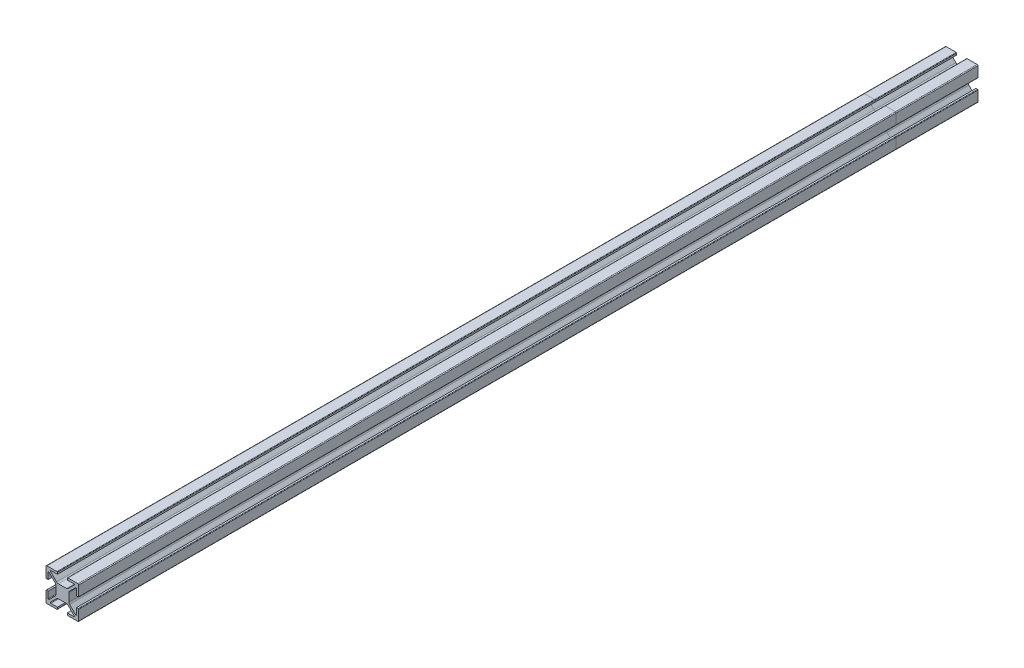
SolidWorks part; units mm, degrees
material "6063-T5"
material "6063-T5"
ref_plane "Front" through (0, 0, 0) normal (0, 0, 1) x (1, 0, 0)
ref_plane "Top" through (0, 0, 0) normal (0, 1, 0) x (1, 0, 0)
ref_plane "Right" through (0, 0, 0) normal (1, 0, 0) x (0, 0, -1)
sketch "Esboço1" plane through (0, 0, 0) normal (1, 0, 0) x (0, 0, -1)
  line L0 (0, 0) -> (-50, 0)
  dimension "D1" = 50
other "Quadrado PF20-21 - PERFIL 2020 T-SLOT 6MM(1)"
ref_plane "Plano1" through (0, 0, 0) normal (0, 0, 1) x (0, -1, 0)
sketch "Esboço11" plane through (0, 0, 0) normal (0, 0, 1) x (0, -1, 0)
  line L0 (8.1879, -7.2686) -> (4.4393, -3.5201)
  line L1 (4, -2.4594) -> (4, 2.4594)
  line L2 (4.4393, 3.5201) -> (8.1879, 7.2686)
  line L3 (8.7, 7.0565) -> (8.7, 3.05)
  line L4 (10, 3.35) -> (10, 9.5)
  line L5 (9.5, 10) -> (3.35, 10)
  line L6 (3.05, 8.7) -> (7.0565, 8.7)
  line L7 (7.2686, 8.1879) -> (3.5201, 4.4393)
  line L8 (2.4594, 4) -> (-2.4594, 4)
  line L9 (-3.5201, 4.4393) -> (-7.2686, 8.1879)
  line L10 (-7.0565, 8.7) -> (-3.05, 8.7)
  line L11 (-3.35, 10) -> (-9.5, 10)
  line L12 (-10, 9.5) -> (-10, 3.35)
  line L13 (-8.7, 3.05) -> (-8.7, 7.0565)
  line L14 (-8.1879, 7.2686) -> (-4.4393, 3.5201)
  line L15 (-4, 2.4594) -> (-4, -2.4594)
  line L16 (-4.4393, -3.5201) -> (-8.1879, -7.2686)
  line L17 (-8.7, -7.0565) -> (-8.7, -3.05)
  line L18 (-10, -3.35) -> (-10, -9.5)
  line L19 (-9.5, -10) -> (-3.35, -10)
  line L20 (-3.05, -8.7) -> (-7.0565, -8.7)
  line L21 (-7.2686, -8.1879) -> (-3.5201, -4.4393)
  line L22 (-2.4594, -4) -> (2.4594, -4)
  line L23 (3.5201, -4.4393) -> (7.2686, -8.1879)
  line L24 (7.0565, -8.7) -> (3.05, -8.7)
  line L25 (3.05, -8.7) -> (3.05, -9.7)
  line L26 (3.35, -10) -> (9.5, -10)
  line L27 (10, -9.5) -> (10, -3.35)
  line L28 (8.7, -3.05) -> (9.7, -3.05)
  line L29 (8.7, -3.05) -> (8.7, -7.0565)
  line L30 (-3.05, 9.7) -> (-3.05, 8.7)
  line L31 (-9.7, -3.05) -> (-8.7, -3.05)
  line L32 (3.05, 9.7) -> (3.05, 8.7)
  line L33 (-9.7, 3.05) -> (-8.7, 3.05)
  line L34 (-3.05, -8.7) -> (-3.05, -9.7)
  line L35 (8.7, 3.05) -> (9.7, 3.05)
  circle A0 centre (0, 0) radius 2.25
  arc A1 (8.1879, -7.2686) -> (8.7, -7.0565) centre (8.4, -7.0565) ccw
  arc A2 (4, -2.4594) -> (4.4393, -3.5201) centre (5.5, -2.4594) ccw
  arc A3 (4.4393, 3.5201) -> (4, 2.4594) centre (5.5, 2.4594) ccw
  arc A4 (8.7, 7.0565) -> (8.1879, 7.2686) centre (8.4, 7.0565) ccw
  arc A5 (10, 9.5) -> (9.5, 10) centre (9.5, 9.5) ccw
  arc A6 (7.2686, 8.1879) -> (7.0565, 8.7) centre (7.0565, 8.4) ccw
  arc A7 (2.4594, 4) -> (3.5201, 4.4393) centre (2.4594, 5.5) ccw
  arc A8 (-3.5201, 4.4393) -> (-2.4594, 4) centre (-2.4594, 5.5) ccw
  arc A9 (-7.0565, 8.7) -> (-7.2686, 8.1879) centre (-7.0565, 8.4) ccw
  arc A10 (-9.5, 10) -> (-10, 9.5) centre (-9.5, 9.5) ccw
  arc A11 (-8.1879, 7.2686) -> (-8.7, 7.0565) centre (-8.4, 7.0565) ccw
  arc A12 (-4, 2.4594) -> (-4.4393, 3.5201) centre (-5.5, 2.4594) ccw
  arc A13 (-4.4393, -3.5201) -> (-4, -2.4594) centre (-5.5, -2.4594) ccw
  arc A14 (-8.7, -7.0565) -> (-8.1879, -7.2686) centre (-8.4, -7.0565) ccw
  arc A15 (-10, -9.5) -> (-9.5, -10) centre (-9.5, -9.5) ccw
  arc A16 (-7.2686, -8.1879) -> (-7.0565, -8.7) centre (-7.0565, -8.4) ccw
  arc A17 (-2.4594, -4) -> (-3.5201, -4.4393) centre (-2.4594, -5.5) ccw
  arc A18 (3.5201, -4.4393) -> (2.4594, -4) centre (2.4594, -5.5) ccw
  arc A19 (7.0565, -8.7) -> (7.2686, -8.1879) centre (7.0565, -8.4) ccw
  arc A20 (9.5, -10) -> (10, -9.5) centre (9.5, -9.5) ccw
  arc A21 (-9.7, 3.05) -> (-10, 3.35) centre (-9.7, 3.35) cw
  arc A22 (-9.7, -3.05) -> (-10, -3.35) centre (-9.7, -3.35) ccw
  arc A23 (-3.05, -9.7) -> (-3.35, -10) centre (-3.35, -9.7) cw
  arc A24 (3.05, -9.7) -> (3.35, -10) centre (3.35, -9.7) ccw
  arc A25 (9.7, -3.05) -> (10, -3.35) centre (9.7, -3.35) cw
  arc A26 (9.7, 3.05) -> (10, 3.35) centre (9.7, 3.35) ccw
  arc A27 (3.05, 9.7) -> (3.35, 10) centre (3.35, 9.7) cw
  arc A28 (-3.05, 9.7) -> (-3.35, 10) centre (-3.35, 9.7) ccw
  point P0 (0, 10)
  point P1 (-10, 10)
  point P2 (0, 0)
  point P3 (10, 10)
  point P4 (10, 0)
  point P5 (10, -10)
  point P6 (0, -10)
  point P7 (-10, -10)
  point P8 (-10, 0)
  point P9 (0, 0)
  point P88 (0, 0)
sketch "Croquis1" plane through (0, 0, 50) normal (0, 0, 1) x (1, 0, 0)
  line L36 (-7.2686, -8.1879) -> (-3.5201, -4.4393)
  line L37 (-2.4594, -4) -> (2.4594, -4)
  line L38 (3.5201, -4.4393) -> (7.2686, -8.1879)
  line L39 (7.0565, -8.7) -> (3.05, -8.7)
  line L40 (3.05, -8.7) -> (3.05, -9.7)
  line L41 (3.35, -10) -> (9.5, -10)
  line L42 (10, -9.5) -> (10, -3.35)
  line L43 (9.7, -3.05) -> (8.7, -3.05)
  line L44 (8.7, -3.05) -> (8.7, -7.0565)
  line L45 (8.1879, -7.2686) -> (4.4393, -3.5201)
  line L46 (4, -2.4594) -> (4, 2.4594)
  line L47 (4.4393, 3.5201) -> (8.1879, 7.2686)
  line L48 (8.7, 7.0565) -> (8.7, 3.05)
  line L49 (8.7, 3.05) -> (9.7, 3.05)
  line L50 (10, 3.35) -> (10, 9.5)
  line L51 (9.5, 10) -> (3.35, 10)
  line L52 (3.05, 9.7) -> (3.05, 8.7)
  line L53 (3.05, 8.7) -> (7.0565, 8.7)
  line L54 (7.2686, 8.1879) -> (3.5201, 4.4393)
  line L55 (2.4594, 4) -> (-2.4594, 4)
  line L56 (-3.5201, 4.4393) -> (-7.2686, 8.1879)
  line L57 (-7.0565, 8.7) -> (-3.05, 8.7)
  line L58 (-3.05, 8.7) -> (-3.05, 9.7)
  line L59 (-3.35, 10) -> (-9.5, 10)
  line L60 (-10, 9.5) -> (-10, 3.35)
  line L61 (-9.7, 3.05) -> (-8.7, 3.05)
  line L62 (-8.7, 3.05) -> (-8.7, 7.0565)
  line L63 (-8.1879, 7.2686) -> (-4.4393, 3.5201)
  line L64 (-4, 2.4594) -> (-4, -2.4594)
  line L65 (-4.4393, -3.5201) -> (-8.1879, -7.2686)
  line L66 (-8.7, -7.0565) -> (-8.7, -3.05)
  line L67 (-8.7, -3.05) -> (-9.7, -3.05)
  line L68 (-10, -3.35) -> (-10, -9.5)
  line L69 (-9.5, -10) -> (-3.35, -10)
  line L70 (-3.05, -9.7) -> (-3.05, -8.7)
  line L71 (-3.05, -8.7) -> (-7.0565, -8.7)
  line L72 (-7.2686, -8.1879) -> (-3.5201, -4.4393)
  line L73 (-2.4594, -4) -> (2.4594, -4)
  line L74 (3.5201, -4.4393) -> (7.2686, -8.1879)
  line L75 (7.0565, -8.7) -> (3.05, -8.7)
  line L76 (3.05, -8.7) -> (3.05, -9.7)
  line L77 (3.35, -10) -> (9.5, -10)
  line L78 (10, -9.5) -> (10, -3.35)
  line L79 (9.7, -3.05) -> (8.7, -3.05)
  line L80 (8.7, -3.05) -> (8.7, -7.0565)
  line L81 (8.1879, -7.2686) -> (4.4393, -3.5201)
  line L82 (4, -2.4594) -> (4, 2.4594)
  line L83 (4.4393, 3.5201) -> (8.1879, 7.2686)
  line L84 (8.7, 7.0565) -> (8.7, 3.05)
  line L85 (8.7, 3.05) -> (9.7, 3.05)
  line L86 (10, 3.35) -> (10, 9.5)
  line L87 (9.5, 10) -> (3.35, 10)
  line L88 (3.05, 9.7) -> (3.05, 8.7)
  line L89 (3.05, 8.7) -> (7.0565, 8.7)
  line L90 (7.2686, 8.1879) -> (3.5201, 4.4393)
  line L91 (2.4594, 4) -> (-2.4594, 4)
  line L92 (-3.5201, 4.4393) -> (-7.2686, 8.1879)
  line L93 (-7.0565, 8.7) -> (-3.05, 8.7)
  line L94 (-3.05, 8.7) -> (-3.05, 9.7)
  line L95 (-3.35, 10) -> (-9.5, 10)
  line L96 (-10, 9.5) -> (-10, 3.35)
  line L97 (-9.7, 3.05) -> (-8.7, 3.05)
  line L98 (-8.7, 3.05) -> (-8.7, 7.0565)
  line L99 (-8.1879, 7.2686) -> (-4.4393, 3.5201)
  line L100 (-4, 2.4594) -> (-4, -2.4594)
  line L101 (-4.4393, -3.5201) -> (-8.1879, -7.2686)
  line L102 (-8.7, -7.0565) -> (-8.7, -3.05)
  line L103 (-8.7, -3.05) -> (-9.7, -3.05)
  line L104 (-10, -3.35) -> (-10, -9.5)
  line L105 (-9.5, -10) -> (-3.35, -10)
  line L106 (-3.05, -9.7) -> (-3.05, -8.7)
  line L107 (-3.05, -8.7) -> (-7.0565, -8.7)
  arc A28 (-7.2686, -8.1879) -> (-7.0565, -8.7) centre (-7.0565, -8.4) ccw
  arc A29 (-2.4594, -4) -> (-3.5201, -4.4393) centre (-2.4594, -5.5) ccw
  arc A30 (3.5201, -4.4393) -> (2.4594, -4) centre (2.4594, -5.5) ccw
  arc A31 (7.0565, -8.7) -> (7.2686, -8.1879) centre (7.0565, -8.4) ccw
  arc A32 (3.05, -9.7) -> (3.35, -10) centre (3.35, -9.7) ccw
  arc A33 (9.5, -10) -> (10, -9.5) centre (9.5, -9.5) ccw
  arc A34 (10, -3.35) -> (9.7, -3.05) centre (9.7, -3.35) ccw
  arc A35 (8.1879, -7.2686) -> (8.7, -7.0565) centre (8.4, -7.0565) ccw
  arc A36 (4, -2.4594) -> (4.4393, -3.5201) centre (5.5, -2.4594) ccw
  arc A37 (4.4393, 3.5201) -> (4, 2.4594) centre (5.5, 2.4594) ccw
  arc A38 (8.7, 7.0565) -> (8.1879, 7.2686) centre (8.4, 7.0565) ccw
  arc A39 (9.7, 3.05) -> (10, 3.35) centre (9.7, 3.35) ccw
  arc A40 (10, 9.5) -> (9.5, 10) centre (9.5, 9.5) ccw
  arc A41 (3.35, 10) -> (3.05, 9.7) centre (3.35, 9.7) ccw
  arc A42 (7.2686, 8.1879) -> (7.0565, 8.7) centre (7.0565, 8.4) ccw
  arc A43 (2.4594, 4) -> (3.5201, 4.4393) centre (2.4594, 5.5) ccw
  arc A44 (-3.5201, 4.4393) -> (-2.4594, 4) centre (-2.4594, 5.5) ccw
  arc A45 (-7.0565, 8.7) -> (-7.2686, 8.1879) centre (-7.0565, 8.4) ccw
  arc A46 (-3.05, 9.7) -> (-3.35, 10) centre (-3.35, 9.7) ccw
  arc A47 (-9.5, 10) -> (-10, 9.5) centre (-9.5, 9.5) ccw
  arc A48 (-10, 3.35) -> (-9.7, 3.05) centre (-9.7, 3.35) ccw
  arc A49 (-8.1879, 7.2686) -> (-8.7, 7.0565) centre (-8.4, 7.0565) ccw
  arc A50 (-4, 2.4594) -> (-4.4393, 3.5201) centre (-5.5, 2.4594) ccw
  arc A51 (-4.4393, -3.5201) -> (-4, -2.4594) centre (-5.5, -2.4594) ccw
  arc A52 (-8.7, -7.0565) -> (-8.1879, -7.2686) centre (-8.4, -7.0565) ccw
  arc A53 (-9.7, -3.05) -> (-10, -3.35) centre (-9.7, -3.35) ccw
  arc A54 (-10, -9.5) -> (-9.5, -10) centre (-9.5, -9.5) ccw
  arc A55 (-3.35, -10) -> (-3.05, -9.7) centre (-3.35, -9.7) ccw
  arc A56 (-7.2686, -8.1879) -> (-7.0565, -8.7) centre (-7.0565, -8.4) ccw
  arc A57 (-2.4594, -4) -> (-3.5201, -4.4393) centre (-2.4594, -5.5) ccw
  arc A58 (3.5201, -4.4393) -> (2.4594, -4) centre (2.4594, -5.5) ccw
  arc A59 (7.0565, -8.7) -> (7.2686, -8.1879) centre (7.0565, -8.4) ccw
  arc A60 (3.05, -9.7) -> (3.35, -10) centre (3.35, -9.7) ccw
  arc A61 (9.5, -10) -> (10, -9.5) centre (9.5, -9.5) ccw
  arc A62 (10, -3.35) -> (9.7, -3.05) centre (9.7, -3.35) ccw
  arc A63 (8.1879, -7.2686) -> (8.7, -7.0565) centre (8.4, -7.0565) ccw
  arc A64 (4, -2.4594) -> (4.4393, -3.5201) centre (5.5, -2.4594) ccw
  arc A65 (4.4393, 3.5201) -> (4, 2.4594) centre (5.5, 2.4594) ccw
  arc A66 (8.7, 7.0565) -> (8.1879, 7.2686) centre (8.4, 7.0565) ccw
  arc A67 (9.7, 3.05) -> (10, 3.35) centre (9.7, 3.35) ccw
  arc A68 (10, 9.5) -> (9.5, 10) centre (9.5, 9.5) ccw
  arc A69 (3.35, 10) -> (3.05, 9.7) centre (3.35, 9.7) ccw
  arc A70 (7.2686, 8.1879) -> (7.0565, 8.7) centre (7.0565, 8.4) ccw
  arc A71 (2.4594, 4) -> (3.5201, 4.4393) centre (2.4594, 5.5) ccw
  arc A72 (-3.5201, 4.4393) -> (-2.4594, 4) centre (-2.4594, 5.5) ccw
  arc A73 (-7.0565, 8.7) -> (-7.2686, 8.1879) centre (-7.0565, 8.4) ccw
  arc A74 (-3.05, 9.7) -> (-3.35, 10) centre (-3.35, 9.7) ccw
  arc A75 (-9.5, 10) -> (-10, 9.5) centre (-9.5, 9.5) ccw
  arc A76 (-10, 3.35) -> (-9.7, 3.05) centre (-9.7, 3.35) ccw
  arc A77 (-8.1879, 7.2686) -> (-8.7, 7.0565) centre (-8.4, 7.0565) ccw
  arc A78 (-4, 2.4594) -> (-4.4393, 3.5201) centre (-5.5, 2.4594) ccw
  arc A79 (-4.4393, -3.5201) -> (-4, -2.4594) centre (-5.5, -2.4594) ccw
  arc A80 (-8.7, -7.0565) -> (-8.1879, -7.2686) centre (-8.4, -7.0565) ccw
  arc A81 (-9.7, -3.05) -> (-10, -3.35) centre (-9.7, -3.35) ccw
  arc A82 (-10, -9.5) -> (-9.5, -10) centre (-9.5, -9.5) ccw
  arc A83 (-3.35, -10) -> (-3.05, -9.7) centre (-3.35, -9.7) ccw
  dimension "D1" = 0
extrude "Saliente-Extruir1" add sketch "Croquis1" along normal blind 500 separate body
